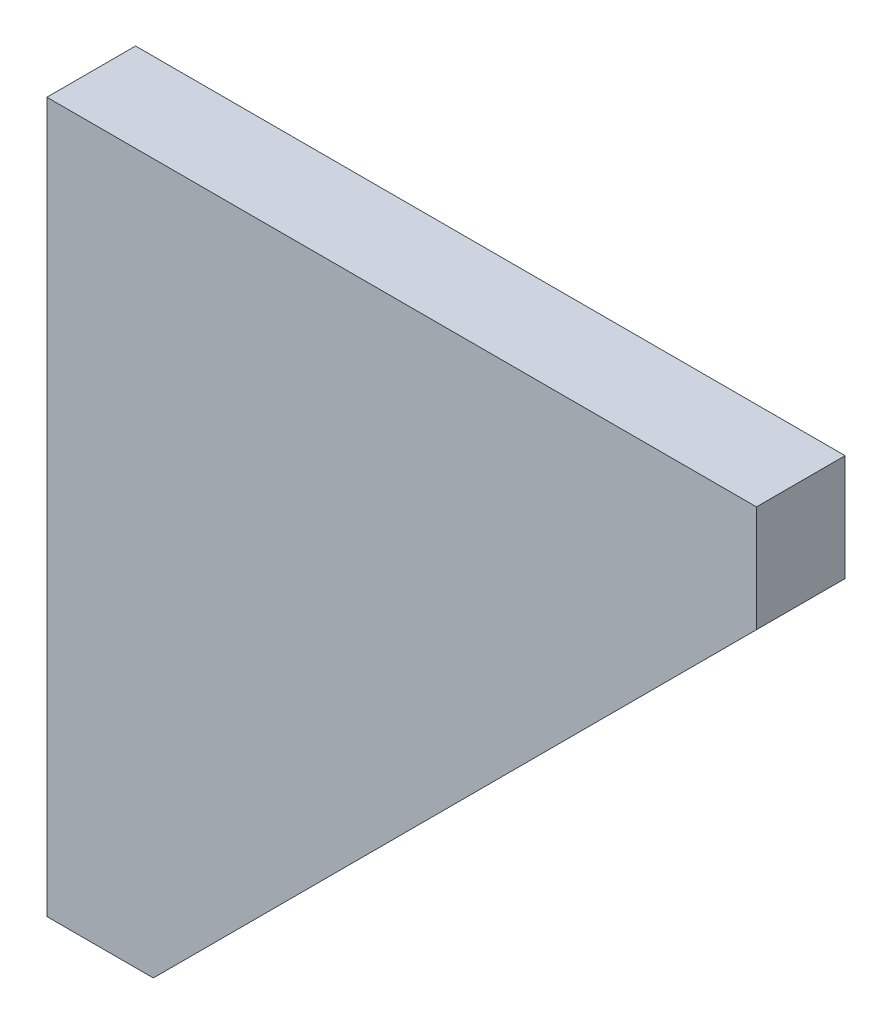
SolidWorks part; units mm, degrees
material "1.0037 (S235JR)"
ref_plane "Płaszczyzna przednia" through (0, 0, 0) normal (0, 0, 1) x (1, 0, 0)
ref_plane "Płaszczyzna górna" through (0, 0, 0) normal (0, 1, 0) x (1, 0, 0)
ref_plane "Płaszczyzna prawa" through (0, 0, 0) normal (1, 0, 0) x (0, 0, -1)
sketch "Szkic1" plane through (0, 0, 0) normal (0, 0, 1) x (1, 0, 0)
  line L0 (-12, -67) -> (-12, 13)
  line L1 (-12, 13) -> (68, 13)
  line L2 (0, 13) -> (220, 13) construction
  line L3 (68, 13) -> (68, 1)
  line L4 (-12, -67) -> (0, -67)
  line L5 (350, 1) -> (0, 1) construction
  line L6 (68, 1) -> (0, -67)
extrude "Dodanie-wyciągnięcie1" add sketch "Szkic1" along normal blind 10
